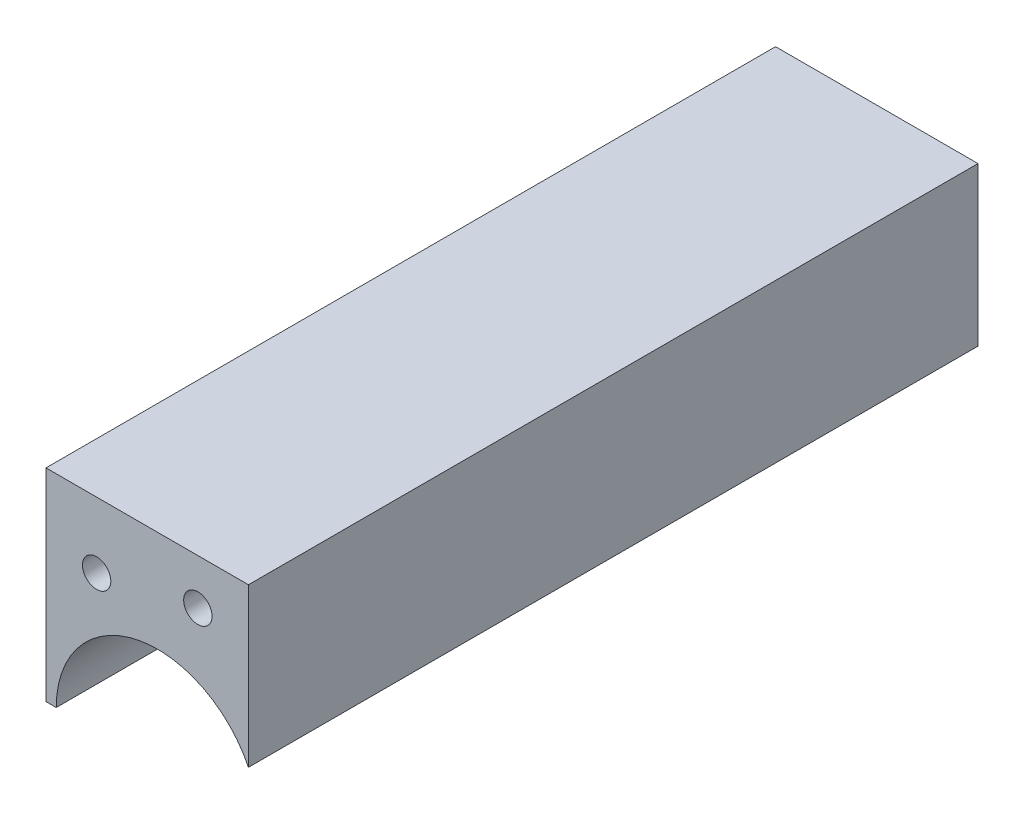
SolidWorks part; units mm, degrees
ref_plane "Front Plane" through (0, 0, 0) normal (0, 0, 1) x (1, 0, 0)
ref_plane "Top Plane" through (0, 0, 0) normal (0, 1, 0) x (1, 0, 0)
ref_plane "Right Plane" through (0, 0, 0) normal (1, 0, 0) x (0, 0, -1)
sketch "Sketch1" plane through (0, 0, 0) normal (0, 0, 1) x (1, 0, 0)
  line L1 (0, 0) -> (1.01, 0)
  line L2 (0, 0) -> (0, 20)
  line L3 (0, 20) -> (20, 20)
  line L4 (20, 4.3795) -> (20, 20)
  arc A0 (20, 4.3795) -> (1.01, 0) centre (11.01, 0) ccw
  circle A3 centre (5, 13.5) radius 1.4
  circle A4 centre (15, 15.5) radius 1.4
extrude "Boss-Extrude1" add sketch "Sketch1" along normal blind 72.07
